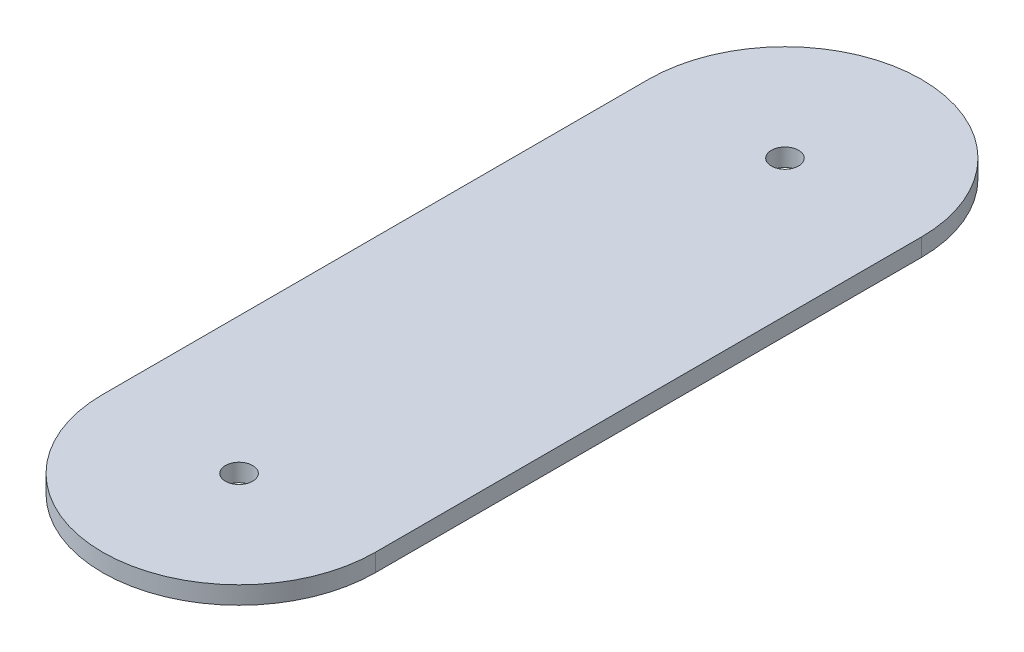
SolidWorks part; units mm, degrees
ref_plane "Front Plane" through (0, 0, 0) normal (0, 0, 1) x (1, 0, 0)
ref_plane "Top Plane" through (0, 0, 0) normal (0, 1, 0) x (1, 0, 0)
ref_plane "Right Plane" through (0, 0, 0) normal (1, 0, 0) x (0, 0, -1)
sketch "Sketch1" plane through (0, 0, 0) normal (0, 1, 0) x (1, 0, 0)
  line L0 (0, 0) -> (0, -101.6)
  line L1 (50.8, 0) -> (50.8, -101.6)
  arc A0 (0, 0) -> (50.8, 0) centre (25.4, 0) cw
  arc A1 (0, -101.6) -> (50.8, -101.6) centre (25.4, -101.6) ccw
  circle A2 centre (25.4, 0) radius 2.54
  circle A3 centre (25.4, -101.6) radius 2.54
  dimension "D2" = 5.08
  dimension "D3" = 5.08
  dimension "D4" = 101.6
  dimension "D1" = 50.8
extrude "Boss-Extrude1" add sketch "Sketch1" along normal blind 3.302
